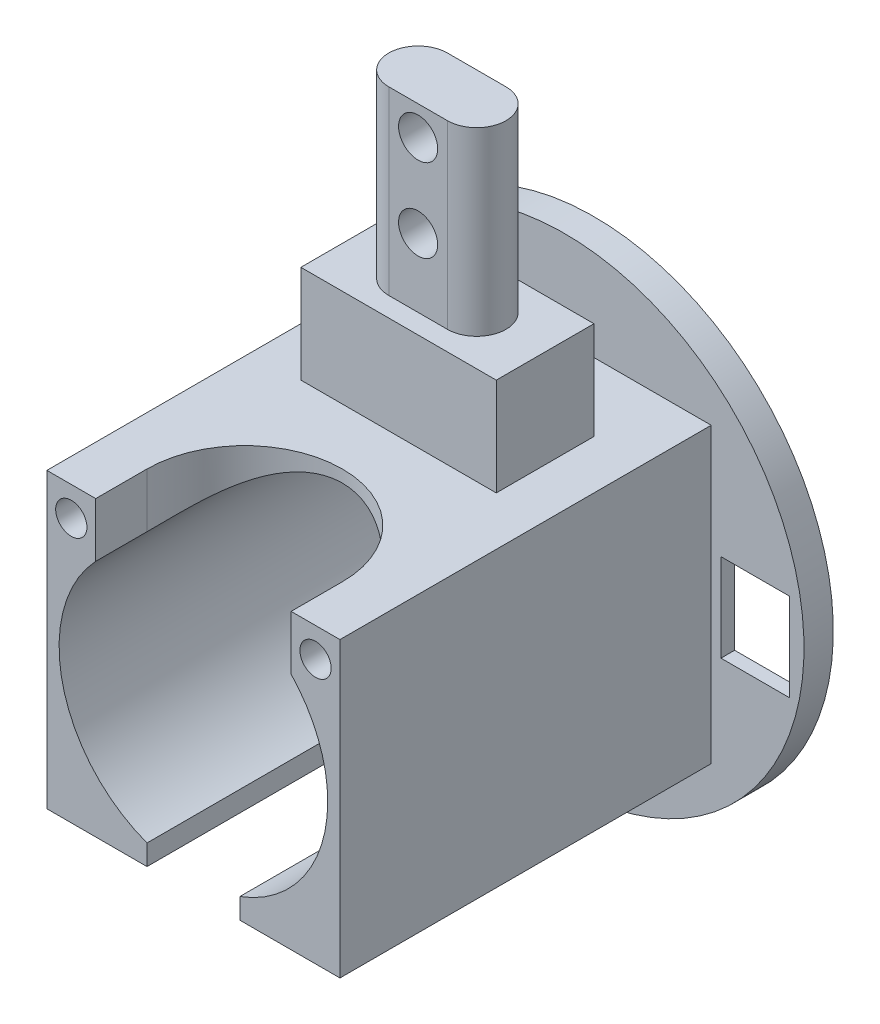
SolidWorks part; units mm, degrees
ref_plane "Ebene vorne" through (0, 0, 0) normal (0, 0, 1) x (1, 0, 0)
ref_plane "Ebene oben" through (0, 0, 0) normal (0, 1, 0) x (1, 0, 0)
ref_plane "Ebene rechts" through (0, 0, 0) normal (1, 0, 0) x (0, 0, -1)
sketch "Sketch1" plane through (0, 0, 0) normal (0, 0, 1) x (1, 0, 0)
  line L1 (-15, 15) -> (15, 15)
  line L2 (-15, 15) -> (-15, -15)
  line L3 (-15, -15) -> (15, -15)
  line L4 (15, 15) -> (15, -15)
  line L5 (0, -15) -> (0, 15) construction
  line L6 (-15, 0) -> (15, 0) construction
  point P0 (0, 0)
  dimension "D1" = 30
  dimension "D2" = 30
extrude "Boss-Extrude1" add sketch "Sketch1" along normal blind 38
sketch "Sketch2" plane through (0, 0, 38) normal (0, 0, 1) x (1, 0, 0)
  circle A0 centre (0, 0) radius 13.25
  dimension "D1" = 26.5
extrude "Cut-Extrude3" cut sketch "Sketch2" against normal up to next
sketch "Sketch4" plane through (0, 0, 38) normal (0, 0, 1) x (1, 0, 0)
  circle A0 centre (0, 0) radius 13.75
  dimension "D1" = 27.5
extrude "Cut-Extrude4" cut sketch "Sketch4" against normal blind 37
sketch "Sketch5" plane through (0, 0, 0) normal (0, 0, -1) x (-1, 0, 0)
  circle A0 centre (0, 0) radius 24.5
  dimension "D1" = 49
extrude "Boss-Extrude4" add sketch "Sketch5" along normal blind 3 contours A0
sketch "Sketch8" plane through (0, 0, -3) normal (0, 0, -1) x (-1, 0, 0)
  circle A0 centre (0, 0) radius 23.75
  dimension "D1" = 47.5
extrude "Cut-Extrude8" cut sketch "Sketch8" against normal blind 1.6
sketch "Sketch9" plane through (0, 0, 0) normal (0, 0, 1) x (1, 0, 0)
  circle A0 centre (0, 0) radius 13.25
  circle A1 centre (0, 0) radius 13.25 construction
  dimension "D1" = 0
extrude "Cut-Extrude9" cut sketch "Sketch9" against normal blind 1.6
sketch "Sketch10" plane through (0, 0, 0) normal (0, 0, 1) x (1, 0, 0)
  line L0 (15, -15) -> (15, 15) construction
  line L1 (23, -5.1477) -> (16, -5.1477)
  line L2 (23, -5.1477) -> (23, 3.8523)
  line L3 (23, 3.8523) -> (16, 3.8523)
  line L4 (16, -5.1477) -> (16, 3.8523)
  line L5 (19.5, 3.8523) -> (19.5, -5.1477) construction
  line L6 (23, -0.6477) -> (16, -0.6477) construction
  point P0 (19.5, -0.6477)
  dimension "D1" = 7
  dimension "D2" = 9
  dimension "D3" = 1
extrude "Cut-Extrude10" cut sketch "Sketch10" against normal up to next
sketch "Sketch12" plane through (0, -15, 0) normal (0, -1, 0) x (-1, 0, 0)
  line L0 (0, -38) -> (0, -17.75) construction
  line L1 (-4.75, -38) -> (-4.75, -17.75)
  line L2 (4.75, -38) -> (4.75, -17.75)
  line L3 (15, -38) -> (-15, -38) construction
  arc A0 (-4.75, -38) -> (4.75, -38) centre (0, -38) ccw
  arc A1 (4.75, -17.75) -> (-4.75, -17.75) centre (0, -17.75) ccw
  point P3 (0, -27.875)
  dimension "D1" = 0
  dimension "D2" = 9.5
  dimension "D3" = 20.25
extrude "Cut-Extrude11" cut sketch "Sketch12" against normal up to next
sketch "Sketch13" plane through (0, 15, 0) normal (0, 1, 0) x (1, 0, 0)
  line L0 (0, -38) -> (0, -32.75) construction
  line L1 (-10, -38) -> (-10, -32.75)
  line L2 (10, -38) -> (10, -32.75)
  line L3 (15, -38) -> (-15, -38) construction
  arc A0 (-10, -38) -> (10, -38) centre (0, -38) ccw
  arc A1 (10, -32.75) -> (-10, -32.75) centre (0, -32.75) ccw
  point P3 (0, -35.375)
  dimension "D3" = 10
  dimension "D1" = 0
  dimension "D2" = 5.25
extrude "Cut-Extrude12" cut sketch "Sketch13" against normal up to next
sketch "Sketch14" plane through (0, 15, 0) normal (0, 1, 0) x (1, 0, 0)
  line L0 (15, 0) -> (-15, 0) construction
  line L1 (10, -7) -> (-10, -7)
  line L2 (10, -7) -> (10, -17)
  line L3 (10, -17) -> (-10, -17)
  line L4 (-10, -7) -> (-10, -17)
  line L5 (0, -17) -> (0, -7) construction
  line L6 (10, -12) -> (-10, -12) construction
  point P0 (0, -12)
  dimension "D1" = 10
  dimension "D2" = 20
  dimension "D3" = 0
  dimension "D4" = 7
extrude "Boss-Extrude5" add sketch "Sketch14" along normal blind 10
sketch "Sketch15" plane through (0, 25, 0) normal (0, 1, 0) x (1, 0, 0)
  line L0 (-3, -12) -> (3, -12) construction
  line L1 (-3, -9) -> (3, -9)
  line L2 (-3, -15) -> (3, -15)
  line L3 (10, -7) -> (-10, -7) construction
  arc A0 (-3, -9) -> (-3, -15) centre (-3, -12) ccw
  arc A1 (3, -15) -> (3, -9) centre (3, -12) ccw
  point P2 (0, -12)
  dimension "D3" = 3
  dimension "D1" = 6
  dimension "D2" = 0
  dimension "D4" = 2
extrude "Boss-Extrude6" add sketch "Sketch15" along normal blind 18.5
sketch "Sketch16" plane through (0, 0, 9) normal (0, 0, -1) x (-1, 0, 0)
  line L0 (-3, 43.5) -> (3, 43.5) construction
  line L2 (-3, 43.5) -> (-3, 25) construction
  circle A0 centre (0, 40.5) radius 2
  circle A1 centre (0, 32) radius 2
  dimension "D1" = 4
  dimension "D2" = 4
  dimension "D3" = 3
  dimension "D4" = 3
  dimension "D5" = 3
  dimension "D6" = 11.5
extrude "Cut-Extrude13" cut sketch "Sketch16" against normal up to next
sketch "Sketch17" plane through (0, 0, 38) normal (0, 0, 1) x (1, 0, 0)
  line L0 (15, -15) -> (15, 15) construction
  line L1 (15, 15) -> (10, 15) construction
  line L3 (-15, 15) -> (-15, -15) construction
  circle A0 centre (12.5, 12) radius 1.6
  circle A1 centre (-12.5, 12) radius 1.6
  dimension "D2" = 3.2
  dimension "D3" = 3.2
  dimension "D6" = 2.5
  dimension "D1" = 0
  dimension "D4" = 2.5
  dimension "D5" = 3
extrude "Cut-Extrude14" cut sketch "Sketch17" against normal blind 10
